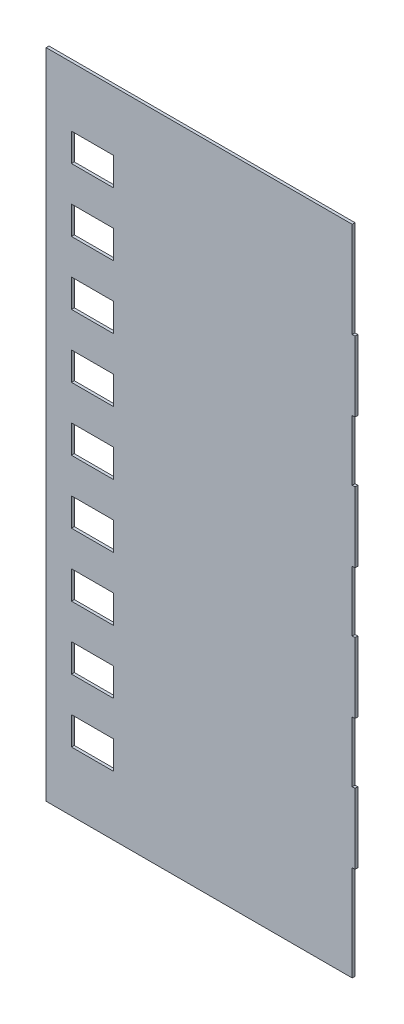
SolidWorks part; units mm, degrees
ref_plane "Front Plane" through (0, 0, 0) normal (0, 0, 1) x (1, 0, 0)
ref_plane "Top Plane" through (0, 0, 0) normal (0, 1, 0) x (1, 0, 0)
ref_plane "Right Plane" through (0, 0, 0) normal (1, 0, 0) x (0, 0, -1)
sketch "Sketch1" plane through (0, 0, 0) normal (0, 0, 1) x (1, 0, 0)
  line L1 (-109, -232.5) -> (109, -232.5)
  line L2 (-109, -232.5) -> (-109, 232.5)
  line L3 (-109, 232.5) -> (109, 232.5)
  line L4 (109, -232.5) -> (109, 232.5)
  line L5 (0, 232.5) -> (0, -232.5) construction
  line L6 (-109, 0) -> (109, 0) construction
  point P0 (0, 0)
  dimension "D1" = 465
  dimension "D2" = 218
extrude "Boss-Extrude1" add sketch "Sketch1" along normal blind 2
sketch "Sketch2" plane through (0, 0, 2) normal (0, 0, 1) x (1, 0, 0)
  line L0 (-109, -232.5) -> (109, -232.5) construction
  line L1 (-109, 232.5) -> (-91, 232.5)
  line L2 (-109, 232.5) -> (-109, -232.5)
  line L3 (-109, -232.5) -> (-91, -232.5)
  line L4 (-91, 232.5) -> (-91, -232.5)
  line L5 (-91, 232.5) -> (-91, 180)
  line L6 (-91, 190) -> (-91, 170)
  line L7 (-91, 170) -> (-91, 135)
  line L8 (-91, 190) -> (-61, 190)
  line L9 (-91, 190) -> (-91, 170)
  line L10 (-91, 170) -> (-61, 170)
  line L11 (-61, 190) -> (-61, 170)
  line L12 (-91, 145) -> (-91, 125)
  line L13 (-91, 100) -> (-91, 80)
  line L14 (-91, 55) -> (-91, 35)
  line L15 (-91, 10) -> (-91, -10)
  line L16 (-91, -35) -> (-91, -55)
  line L17 (-91, -80) -> (-91, -100)
  line L18 (-91, -125) -> (-91, -145)
  line L19 (-91, -170) -> (-91, -190)
  line L21 (-91, 145) -> (-61, 145)
  line L22 (-91, 145) -> (-91, 125)
  line L23 (-91, 125) -> (-61, 125)
  line L24 (-61, 145) -> (-61, 125)
  line L25 (-91, 100) -> (-61, 100)
  line L26 (-91, 100) -> (-91, 80)
  line L27 (-91, 80) -> (-61, 80)
  line L28 (-61, 100) -> (-61, 80)
  line L29 (-91, 55) -> (-61, 55)
  line L30 (-91, 55) -> (-91, 35)
  line L31 (-91, 35) -> (-61, 35)
  line L32 (-61, 55) -> (-61, 35)
  line L33 (-91, 10) -> (-61, 10)
  line L34 (-91, 10) -> (-91, -10)
  line L35 (-91, -10) -> (-61, -10)
  line L36 (-61, 10) -> (-61, -10)
  line L37 (-91, -35) -> (-61, -35)
  line L38 (-91, -35) -> (-91, -55)
  line L39 (-91, -55) -> (-61, -55)
  line L40 (-61, -35) -> (-61, -55)
  line L41 (-91, -80) -> (-61, -80)
  line L42 (-91, -80) -> (-91, -100)
  line L43 (-91, -100) -> (-61, -100)
  line L44 (-61, -80) -> (-61, -100)
  line L45 (-91, -125) -> (-61, -125)
  line L46 (-91, -125) -> (-91, -145)
  line L47 (-91, -145) -> (-61, -145)
  line L48 (-61, -125) -> (-61, -145)
  line L49 (-91, -170) -> (-61, -170)
  line L50 (-91, -170) -> (-91, -190)
  line L51 (-91, -190) -> (-61, -190)
  line L52 (-61, -170) -> (-61, -190)
  point P9 (-91, 180)
  point P12 (-91, 90)
  point P14 (-91, 45)
  point P15 (-91, 0)
  point P16 (-91, -45)
  point P17 (-91, -90)
  point P18 (-91, -135)
  point P19 (-91, -180)
  point P20 (-91, -232.5)
  point P24 (-91, 135)
  point P27 (-91, 90)
  point P30 (-91, 45)
  point P33 (-91, 0)
  point P36 (-91, -45)
  point P39 (-91, -90)
  point P42 (-91, -135)
  point P45 (-91, -180)
  dimension "D1" = 465
  dimension "D2" = 18
  dimension "D3" = 52.5
  dimension "D4" = 20
  dimension "D5" = 30
  dimension "D6" = 45
  dimension "D7" = 45
  dimension "D8" = 45
  dimension "D9" = 45
  dimension "D10" = 45
  dimension "D11" = 45
  dimension "D12" = 45
  dimension "D13" = 45
  dimension "D14" = 52.5
  dimension "D15" = 20
  dimension "D16" = 20
  dimension "D17" = 20
  dimension "D18" = 20
  dimension "D19" = 20
  dimension "D20" = 20
  dimension "D21" = 20
  dimension "D22" = 20
extrude "Cut-Extrude1" cut sketch "Sketch2" against normal blind 8 contours L11 L8 L5 L4 L10 | L24 L21 L7 L4 L23 | L28 L25 L4 L27 | L32 L29 L4 L31 | L36 L33 L4 L35 | L40 L37 L4 L39 | L44 L41 L4 L43 | L48 L45 L4 L47 | L52 L49 L4 L51
sketch "Sketch3" plane through (0, 0, 2) normal (0, 0, 1) x (1, 0, 0)
  line L0 (109, 232.5) -> (109, 139.5)
  line L1 (109, -232.5) -> (109, 232.5) construction
  line L2 (109, 139.5) -> (109, 46.5)
  line L3 (109, 46.5) -> (109, -46.5)
  line L4 (109, -46.5) -> (109, -139.5)
  line L6 (107, 164.5) -> (111, 164.5)
  line L7 (107, 164.5) -> (107, 114.5)
  line L8 (107, 114.5) -> (111, 114.5)
  line L9 (111, 164.5) -> (111, 114.5)
  line L10 (109, 114.5) -> (109, 164.5) construction
  line L11 (107, 139.5) -> (111, 139.5) construction
  line L12 (107, 71.5) -> (111, 71.5)
  line L13 (107, 71.5) -> (107, 21.5)
  line L14 (107, 21.5) -> (111, 21.5)
  line L15 (111, 71.5) -> (111, 21.5)
  line L16 (109, 21.5) -> (109, 71.5) construction
  line L17 (107, 46.5) -> (111, 46.5) construction
  line L18 (107, -21.5) -> (111, -21.5)
  line L19 (107, -21.5) -> (107, -71.5)
  line L20 (107, -71.5) -> (111, -71.5)
  line L21 (111, -21.5) -> (111, -71.5)
  line L22 (109, -71.5) -> (109, -21.5) construction
  line L23 (107, -46.5) -> (111, -46.5) construction
  line L24 (107, -114.5) -> (111, -114.5)
  line L25 (107, -114.5) -> (107, -164.5)
  line L26 (107, -164.5) -> (111, -164.5)
  line L27 (111, -114.5) -> (111, -164.5)
  line L28 (109, -164.5) -> (109, -114.5) construction
  line L29 (107, -139.5) -> (111, -139.5) construction
  line M25 (109, -232.5) -> (109, 232.5)
  dimension "D1" = 93
  dimension "D2" = 93
  dimension "D3" = 93
  dimension "D4" = 93
  dimension "D5" = 50
  dimension "D6" = 50
  dimension "D7" = 50
  dimension "D8" = 50
  dimension "D9" = 4
  dimension "D10" = 4
  dimension "D11" = 4
  dimension "D12" = 4
extrude "Boss-Extrude2" add sketch "Sketch3" against normal blind 2 contours L9 L6 L2 L8 M25 | L15 L12 L3 L14 M25 | L27 L24 L26 M25 | L21 L18 L4 L20 M25
